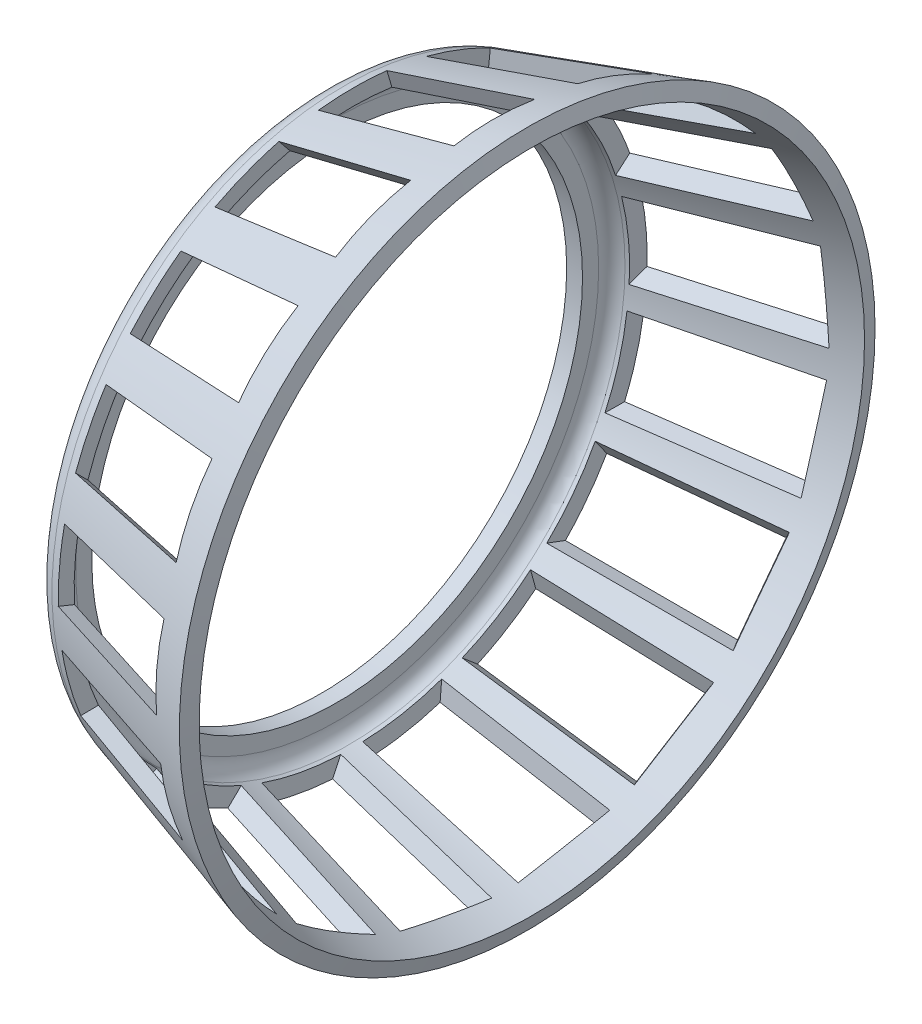
SolidWorks part; units mm, degrees
ref_plane "Plan1" through (0, 0, 0) normal (0, 0, 1) x (1, 0, 0)
ref_plane "Plan2" through (0, 0, 0) normal (0, 1, 0) x (1, 0, 0)
ref_plane "Plan3" through (0, 0, 0) normal (1, 0, 0) x (0, 0, -1)
sketch "Esquisse1" plane through (0, 0, 0) normal (0, 0, 1) x (1, 0, 0)
  line L0 (-13.6917, 18.4327) -> (-2.1012, 21.9763)
  line L1 (-15.1069, 16.5201) -> (-15.1069, 15.5)
  line L2 (-2.1012, 21.9763) -> (-1.8088, 21.02)
  line L3 (-1.8088, 21.02) -> (-13.3993, 17.4764)
  line L4 (-14.1069, 16.5201) -> (-14.1069, 15.5)
  line L5 (-14.1069, 15.5) -> (-15.1069, 15.5)
  line L6 (0, 0) -> (-24.8427, 0) construction
  arc A0 (-14.1069, 16.5201) -> (-13.3993, 17.4764) centre (-13.1069, 16.5201) cw
  arc A1 (-15.1069, 16.5201) -> (-13.6917, 18.4327) centre (-13.1069, 16.5201) cw
  point P13 (-15.1069, 18)
  dimension "D4" = 1
  dimension "D7" = 2
  dimension "D1" = 1
  dimension "D2" = 17
  dimension "D3" = 18
  dimension "D5" = 1
  dimension "D6" = 15.5
  dimension "D8" = 13.6
  dimension "D9" = 15.1069
revolve "Base-Révolution" add sketch "Esquisse1" angle 360 about L6
sketch "Esquisse3" plane through (0, 0, 0) normal (0, 0, 1) x (1, 0, 0)
  line L0 (-2.1012, 21.6811) -> (-10.5063, 19.1114) construction
  line L1 (-2.1012, 21.9763) -> (-2.1012, -21.9763) construction
  line L2 (0, 0) -> (-4.9435, 0) construction
  dimension "D1" = 17
ref_plane "Plan4" through (-7.8964, 20.2045, 0) normal (-0.2924, 0.9563, 0) x (0, 0, -1)
sketch "Esquisse4" plane through (-7.8964, 20.2045, 0) normal (-0.2924, 0.9563, 0) x (0, 0, -1)
  line L0 (0, 0) -> (0, -4.9347) construction
  line L1 (0, -1.6442) -> (0, 22.1131) construction
  line L2 (0, -3.5403) -> (0, -3.0405) construction
  line L3 (2.125, 5.4649) -> (2.4884, -3.7851)
  line L4 (-2.125, 5.4649) -> (-2.4884, -3.7851)
  line L5 (-2.125, 5.4649) -> (2.125, 5.4649)
  line L6 (2.4884, -3.7851) -> (-2.4884, -3.7851)
  point P9 (0, -3.76)
  point P12 (0, 5.4764)
  dimension "D1" = 4.5
  dimension "D2" = 4.25
  dimension "D3" = 9.25
extrude "Enlèv. mat.-Extru.1" cut sketch "Esquisse4" against normal blind 2 draft 20
pattern_circular "Répétition circulaire1" count 17 every 21.176 about axis through (0, 0, 0) along (-1, 0, 0)
